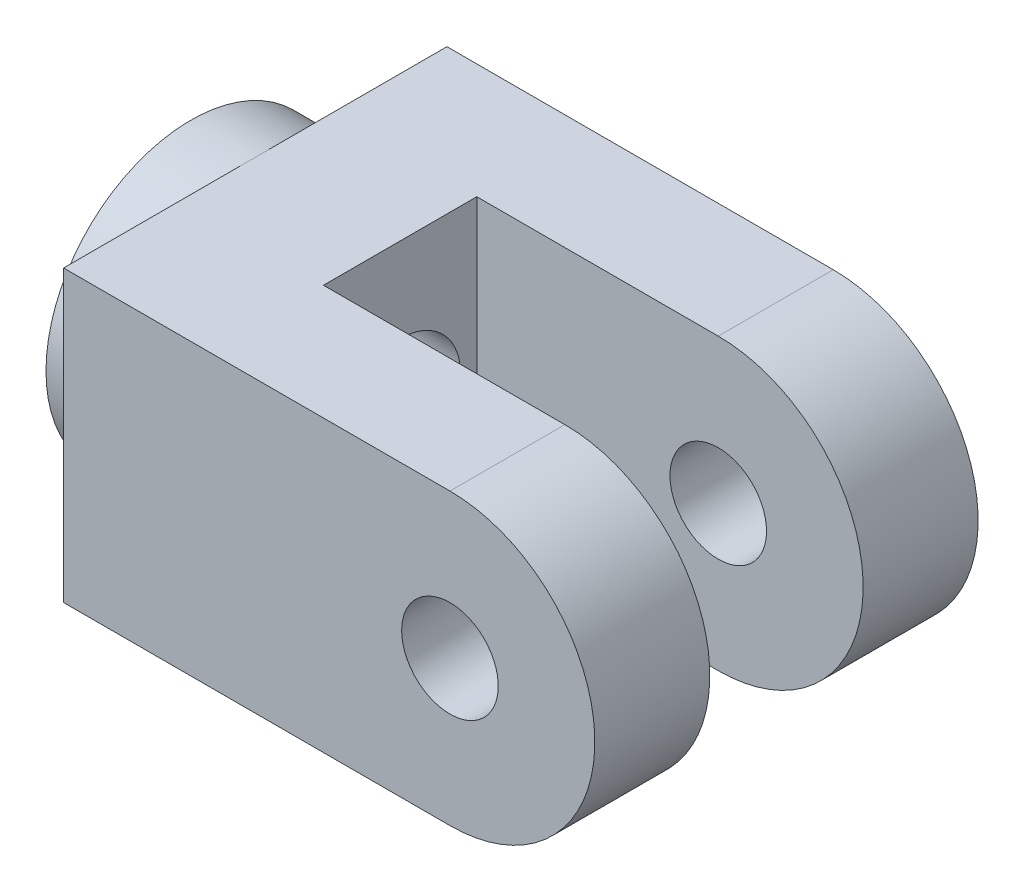
SolidWorks part; units mm, degrees
ref_plane "Front Plane" through (0, 0, 0) normal (0, 0, 1) x (1, 0, 0)
ref_plane "Top Plane" through (0, 0, 0) normal (0, 1, 0) x (1, 0, 0)
ref_plane "Right Plane" through (0, 0, 0) normal (1, 0, 0) x (0, 0, -1)
sketch "Sketch1" plane through (0, 0, 0) normal (0, 0, 1) x (1, 0, 0)
  line L1 (-66, 36) -> (66, 36)
  line L2 (-66, 36) -> (-66, -36)
  line L3 (-66, -36) -> (66, -36)
  line L4 (66, 36) -> (66, -36)
  line L5 (-66, 36) -> (66, -36) construction
  line L6 (-66, -36) -> (66, 36) construction
  point P0 (0, 0)
extrude "Boss-Extrude1" add sketch "Sketch1" along normal mid plane 95.25
sketch "Sketch2" plane through (0, 0, -47.625) normal (0, 0, -1) x (-1, 0, 0)
  line L0 (-66, 36) -> (66, 36) construction
  line L1 (66, -36) -> (-66, -36) construction
  line L2 (-66, -36) -> (-66, 36) construction
  arc A0 (-30, 36) -> (-30, -36) centre (-30, 0) ccw
  dimension "D1" = 36
extrude "Cut-Extrude1" cut sketch "Sketch2" along normal through all and the other way through all flip side to cut
sketch "Sketch3" plane through (0, 36, 0) normal (0, 1, 0) x (1, 0, 0)
  line L0 (66, -47.625) -> (66, 47.625) construction
  line L1 (-30, 19.045) -> (66, 19.045)
  line L2 (-30, 19.045) -> (-30, -19.055)
  line L3 (-30, -19.055) -> (66, -19.055)
  line L4 (66, 19.045) -> (66, -19.055)
  line L5 (66, 19.045) -> (66, 47.625)
  line L6 (66, 47.625) -> (30, 47.625) construction
  line L7 (30, -47.625) -> (30, 47.625) construction
  line M7 (30, -47.625) -> (30, 47.625)
  dimension "D1" = 38.1
  dimension "D2" = 28.58
  dimension "D3" = 60
extrude "Cut-Extrude2" cut sketch "Sketch3" against normal through all contours L2 L3 L1 M7 | L4 L1 L3 M7
sketch "Sketch4" plane through (-66, 0, 0) normal (-1, 0, 0) x (0, 0, 1)
  circle A0 centre (0, 0) radius 15
extrude "Cut-Extrude3" cut sketch "Sketch4" against normal through all
sketch "Sketch5" plane through (-66, 0, 0) normal (-1, 0, 0) x (0, 0, 1)
  circle A0 centre (0, 0) radius 36
  circle A1 centre (0, 0) radius 15
extrude "Boss-Extrude6" add sketch "Sketch5" along normal blind 16 contours A0 | A1
sketch "Sketch6" plane through (0, 0, -47.625) normal (0, 0, -1) x (-1, 0, 0)
  circle A2 centre (-30, 0) radius 12
extrude "Cut-Extrude4" cut sketch "Sketch6" against normal through all
